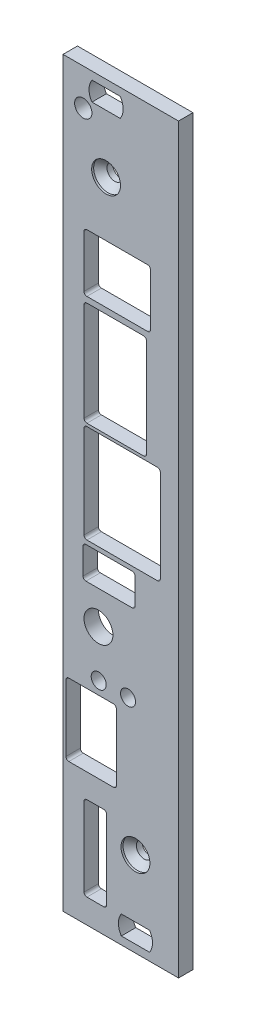
SolidWorks part; units mm, degrees
ref_plane "Front Plane" through (0, 0, 0) normal (0, 0, 1) x (1, 0, 0)
ref_plane "Top Plane" through (0, 0, 0) normal (0, 1, 0) x (1, 0, 0)
ref_plane "Right Plane" through (0, 0, 0) normal (1, 0, 0) x (0, 0, -1)
ref_plane "Plane1" through (0, 0, 2.5) normal (0, 0, 1) x (1, 0, 0)
sketch "Sketch1" plane through (0, 0, 2.5) normal (0, 0, 1) x (1, 0, 0)
  line L0 (12.53, 125.4) -> (-7.45, 125.4)
  line L1 (-7.45, 125.4) -> (-7.45, -3)
  line L2 (-7.45, -3) -> (12.53, -3)
  line L3 (12.53, -3) -> (12.53, 125.4)
extrude "Boss-Extrude1" add sketch "Sketch1" against normal blind 2.5
sketch "Sketch2" plane through (0, 0, 2.5) normal (0, 0, 1) x (1, 0, 0)
  line L0 (2.4454, 124.05) -> (-2.4454, 124.05)
  line L1 (-2.4454, 120.75) -> (2.4454, 120.75)
  arc A0 (-2.4454, 124.05) -> (-2.4454, 120.75) centre (0, 122.4) ccw
  arc A1 (2.4454, 120.75) -> (2.4454, 124.05) centre (0, 122.4) ccw
extrude "Cut-Extrude1" cut sketch "Sketch2" against normal through all
sketch "Sketch3" plane through (0, 0, 2.5) normal (0, 0, 1) x (1, 0, 0)
  line L0 (7.5254, 1.65) -> (2.6346, 1.65)
  line L1 (2.6346, -1.65) -> (7.5254, -1.65)
  arc A0 (2.6346, 1.65) -> (2.6346, -1.65) centre (5.08, 0) ccw
  arc A1 (7.5254, -1.65) -> (7.5254, 1.65) centre (5.08, 0) ccw
extrude "Cut-Extrude2" cut sketch "Sketch3" against normal through all
sketch "Sketch4" plane through (0, 0, 0) normal (0, 0, -1) x (-1, 0, 0)
  line L0 (3.82, 15.8) -> (-0.08, 15.8)
  line L1 (-0.08, 15.8) -> (-0.08, 1.2)
  line L2 (-0.08, 1.2) -> (3.82, 1.2)
  line L3 (3.82, 1.2) -> (3.82, 15.8)
extrude "Cut-Extrude3" cut sketch "Sketch4" against normal through all
hole_wizard "Ø3.0 (3) Diameter Hole1" positions "Sketch6" profile "Sketch5" hole size "Ø3.0" standard "ANSI Metric"
sketch "Sketch6" plane through (0, 0, 2.5) normal (0, 0, 1) x (1, 0, 0)
  point P0 (-3.95, 119.1)
sketch "Sketch5" plane through (-3.95, 119.1, 2.5) normal (1, 0, 0) x (0, -1, 0)
  line L0 (0, 0) -> (0, 2.5)
  line L1 (0, 2.5) -> (1.5, 2.5)
  line L2 (1.5, 2.5) -> (1.5, 0)
  line L5 (1.5, 0) -> (0, 0)
  line L11 (0, -6.35) -> (0, 107.95) construction
  dimension "Thru Hole Dia." = 3
  dimension "Thru Hole Depth" = 2.5
hole_wizard "CSK for M2.5 Flat Head Machine Screw1" positions "Sketch8" profile "Sketch7" countersink size "M2.5" standard "ANSI Metric"
sketch "Sketch8" plane through (0, 0, 2.5) normal (0, 0, 1) x (1, 0, 0)
  point P0 (5.08, 11.7)
  point P1 (0, 110.7)
sketch "Sketch7" plane through (5.08, 11.7, 2.5) normal (1, 0, 0) x (0, -1, 0)
  line L0 (0, 0) -> (0, 2.5)
  line L1 (0, 2.5) -> (1.35, 2.5)
  line L2 (1.35, 2.5) -> (1.35, 1.5)
  line L3 (1.35, 1.5) -> (2.5, 0.35)
  line L4 (2.5, 0.35) -> (2.5, 0)
  line L6 (2.5, 0) -> (0, 0)
  line L7 (-1.35, 1.5) -> (-2.5, 0.35) construction
  line L11 (0, -6.35) -> (0, 107.95) construction
  dimension "Thru Hole Dia." = 2.7
  dimension "Thru Hole Depth" = 2.5
  dimension "C'Sink Dia." = 5
  dimension "C'Sink Angle" = 90
  dimension "Head Clearance" = 0.35
ref_plane "Board bottom" through (0, 11.2, 0) normal (0, -1, 0) x (-1, 0, 0)
ref_plane "Board top" through (0, 111.2, 0) normal (0, 1, 0) x (1, 0, 0)
ref_plane "Board upper surface" through (-3.82, 0, 0) normal (1, 0, 0) x (0, 0, -1)
ref_plane "Board lower surface" through (-5.42, 0, 0) normal (1, 0, 0) x (0, 0, -1)
sketch "Sketch9" plane through (0, 0, 2.5) normal (0, 0, 1) x (1, 0, 0)
  line L0 (-3.82, 19.95) -> (-3.82, 32.45) construction
  line L1 (-3.82, 19.95) -> (1.78, 19.95)
  line L2 (-3.82, 32.45) -> (1.78, 32.45)
  line L3 (1.78, 19.95) -> (1.78, 32.45)
  line L4 (-3.82, -47.3899) -> (-3.82, 47.3899) construction
  line L5 (-28.8918, 11.2) -> (28.8918, 11.2) construction
  line L6 (-3.82, 32.45) -> (-3.82, 19.95) construction
  line L7 (-3.82, 32.45) -> (-6.95, 32.45)
  line L8 (-3.82, 19.95) -> (-6.95, 19.95)
  line L9 (-6.95, 32.45) -> (-6.95, 19.95)
  line L10 (-6.95, 32.45) -> (1.78, 19.95) construction
  line L11 (1.78, 32.45) -> (-6.95, 19.95) construction
  line L12 (-7.45, 125.4) -> (-7.45, -3) construction
  point P8 (-2.585, 26.2)
  dimension "D1" = 8.75
  dimension "D2" = 21.25
  dimension "D3" = 5.6
  dimension "D4" = 3.13
  dimension "D5" = 15
  dimension "D6" = 1.235
  dimension "D7" = 12.5
  dimension "D8" = 8.73
  dimension "D9" = 0.5
extrude "USB" cut sketch "Sketch9" against normal through all
sketch "Sketch10" plane through (0, 0, 2.5) normal (0, 0, 1) x (1, 0, 0)
  line L0 (-3.82, 34.65) -> (3.8, 34.65) construction
  line L1 (-3.82, -47.3899) -> (-3.82, 47.3899) construction
  line L3 (-28.8918, 11.2) -> (28.8918, 11.2) construction
  circle A0 centre (-1.28, 34.65) radius 1.3
  circle A1 centre (3.8, 34.65) radius 1.3
  dimension "D1" = 2.6
  dimension "D2" = 2.6
  dimension "D3" = 2.54
  dimension "D4" = 5.08
  dimension "D5" = 23.45
extrude "LEDs" cut sketch "Sketch10" against normal through all
sketch "Sketch11" plane through (0, 0, 2.5) normal (0, 0, 1) x (1, 0, 0)
  line L0 (-1.32, 42.7) -> (-3.82, 42.7) construction
  line L1 (-3.82, -47.3899) -> (-3.82, 47.3899) construction
  line L3 (-28.8918, 11.2) -> (28.8918, 11.2) construction
  circle A0 centre (-1.32, 42.7) radius 2.5
  dimension "D1" = 5
  dimension "D2" = 2.5
  dimension "D3" = 31.5
extrude "Reset switch" cut sketch "Sketch11" against normal through all
sketch "Sketch13" plane through (0, 0, 2.5) normal (0, 0, 1) x (1, 0, 0)
  line L0 (0.505, 51.2) -> (-3.82, 51.2) construction
  line L1 (-3.82, -47.3899) -> (-3.82, 47.3899) construction
  line L2 (-28.8918, 11.2) -> (28.8918, 11.2) construction
  line L4 (-3.995, 48.45) -> (5.005, 48.45)
  line L5 (-3.995, 48.45) -> (-3.995, 53.95)
  line L6 (-3.995, 53.95) -> (5.005, 53.95)
  line L7 (5.005, 48.45) -> (5.005, 53.95)
  line L8 (-3.995, 48.45) -> (5.005, 53.95) construction
  line L9 (-3.995, 53.95) -> (5.005, 48.45) construction
  point P1 (0.505, 51.2)
  dimension "D1" = 5.5
  dimension "D2" = 40
  dimension "D3" = 4.325
  dimension "D4" = 9
extrude "Disable comms" cut sketch "Sketch13" against normal through all
sketch "Sketch14" plane through (0, 0, 2.5) normal (0, 0, 1) x (1, 0, 0)
  line L0 (-3.82, 54.7) -> (-3.82, 71.7)
  line L1 (-3.82, 54.7) -> (9.38, 54.7)
  line L2 (-3.82, 71.7) -> (9.38, 71.7)
  line L3 (9.38, 54.7) -> (9.38, 71.7)
  line L4 (-3.82, -47.3899) -> (-3.82, 47.3899) construction
  line L5 (-28.8918, 11.2) -> (28.8918, 11.2) construction
  dimension "D1" = 43.5
  dimension "D2" = 60.5
  dimension "D3" = 13.2
extrude "RJ45" cut sketch "Sketch14" against normal through all
sketch "Sketch15" plane through (0, 0, 2.5) normal (0, 0, 1) x (1, 0, 0)
  line L0 (-3.82, 72.2) -> (-3.82, 90.2)
  line L1 (-3.82, 72.2) -> (6.98, 72.2)
  line L2 (-3.82, 90.2) -> (6.98, 90.2)
  line L3 (6.98, 72.2) -> (6.98, 90.2)
  line L4 (-3.82, -47.3899) -> (-3.82, 47.3899) construction
  line L5 (-28.8918, 11.2) -> (28.8918, 11.2) construction
  dimension "D1" = 61
  dimension "D2" = 79
  dimension "D3" = 10.8
extrude "Output" cut sketch "Sketch15" against normal through all
sketch "Sketch16" plane through (0, 0, 2.5) normal (0, 0, 1) x (1, 0, 0)
  line L0 (-3.82, 91.2) -> (-3.82, 101.2)
  line L1 (-3.82, 91.2) -> (7.68, 91.2)
  line L2 (-3.82, 101.2) -> (7.68, 101.2)
  line L3 (7.68, 91.2) -> (7.68, 101.2)
  line L4 (-3.82, -47.3899) -> (-3.82, 47.3899) construction
  line L5 (-28.8918, 11.2) -> (28.8918, 11.2) construction
  dimension "D1" = 80
  dimension "D2" = 90
  dimension "D3" = 11.5
extrude "Power" cut sketch "Sketch16" against normal through all
fillet "Fillets" radius 0.5 24 edges at (1.78, 19.95, 1.25) (-6.95, 19.95, 1.25) (-6.95, 32.45, 1.25) (1.78, 32.45, 1.25) (0.08, 1.2, 1.25) (-3.82, 1.2, 1.25) (-3.82, 15.8, 1.25) (0.08, 15.8, 1.25) (9.38, 71.7, 1.25) (6.98, 90.2, 1.25) (7.68, 101.2, 1.25) (-3.82, 71.7, 1.25) (-3.82, 90.2, 1.25) (-3.82, 101.2, 1.25) (-3.82, 54.7, 1.25) (-3.82, 72.2, 1.25) (-3.82, 91.2, 1.25) (9.38, 54.7, 1.25) (6.98, 72.2, 1.25) (7.68, 91.2, 1.25) (-3.995, 48.45, 1.25) (5.005, 48.45, 1.25) (5.005, 53.95, 1.25) (-3.995, 53.95, 1.25)
equation "\"D6@Sketch9\"=2.47/2"
